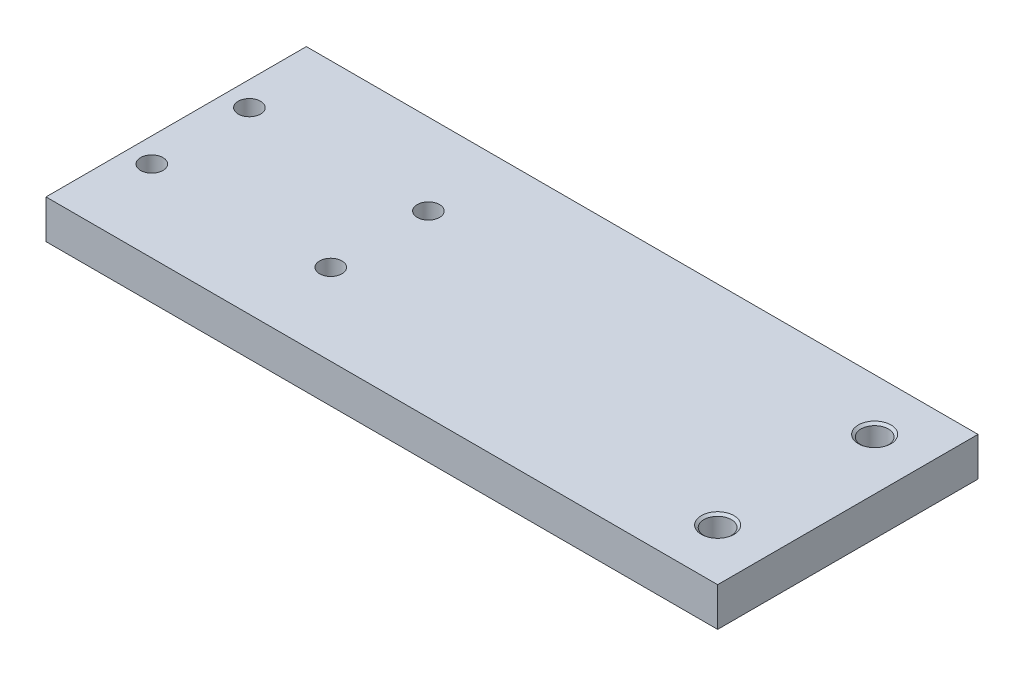
SolidWorks part; units mm, degrees
material "6061 Alloy"
ref_plane "Front" through (0, 0, 0) normal (0, 0, 1) x (1, 0, 0)
ref_plane "Top" through (0, 0, 0) normal (0, 1, 0) x (1, 0, 0)
ref_plane "Right" through (0, 0, 0) normal (1, 0, 0) x (0, 0, -1)
sketch "Sketch1" plane through (0, 0, 0) normal (0, 1, 0) x (1, 0, 0)
  line L1 (0, 0) -> (165.1, 0)
  line L2 (0, 0) -> (0, 64)
  line L3 (0, 64) -> (165.1, 64)
  line L4 (165.1, 0) -> (165.1, 64)
  dimension "D1" = 165.1
  dimension "D2" = 64
extrude "Boss-Extrude1" add sketch "Sketch1" along normal blind 9.525
hole_wizard "1/4 Clearance Hole1" positions "Sketch4" profile "Sketch5" hole size "1/4" standard "ANSI Inch" end condition through all
sketch "Sketch4" plane through (0, 9.525, 0) normal (0, 1, 0) x (1, 0, 0)
  line L0 (152.4, 64) -> (152.4, 51.3) construction
  line L1 (165.1, 64) -> (0, 64) construction
  line L2 (152.4, 51.3) -> (165.1, 51.3) construction
  line L3 (165.1, 0) -> (165.1, 64) construction
  line L5 (165.1, 12.7) -> (152.4, 12.7) construction
  line L6 (152.4, 12.7) -> (152.4, 0) construction
  line L7 (0, 0) -> (165.1, 0) construction
  point P0 (152.4, 51.3)
  point P2 (152.4, 12.7)
  dimension "D1" = 12.7
sketch "Sketch5" plane through (152.4, 9.525, -51.3) normal (1, 0, 0) x (0, 0, 1)
  line L0 (0, 0) -> (0, 9.525)
  line L1 (0, 9.525) -> (3.3782, 9.525)
  line L2 (3.3782, 9.525) -> (3.3782, 0.5328)
  line L3 (3.3782, 0.5328) -> (4.0132, 0)
  line L5 (4.0132, 0) -> (0, 0)
  line L6 (-3.3782, 0.5328) -> (-4.0132, 0) construction
  line L11 (0, -6.35) -> (0, 107.95) construction
  dimension "Thru Hole Dia." = 6.7564
  dimension "Thru Hole Depth" = 9.525
  dimension "Near C'Sink Dia." = 8.0264
  dimension "Near C'Sink Angle" = 100
hole_wizard "CBORE for M5 SHCS1" positions "Sketch8" profile "Sketch7" counterbore size "M5" standard "ANSI Metric" end condition through all
sketch "Sketch8" plane through (0, 0, 0) normal (0, -1, 0) x (-1, 0, 0)
  line L0 (0, 50) -> (0, -50) construction
  line L1 (-6, 44) -> (-6, 20) construction
  line L2 (-6, 20) -> (-6, 32) construction
  line L3 (-6, 32) -> (0, 32) construction
  line L4 (0, 64) -> (0, 0) construction
  point P0 (-6, 44)
  point P2 (-50, 44)
  point P4 (-50, 20)
  point P6 (-6, 20)
  point P25 (0, 0)
  dimension "D1" = 6
  dimension "D2" = 44
  dimension "D3" = 24
sketch "Sketch7" plane through (6, 0, -44) normal (1, 0, 0) x (0, 0, -1)
  line L0 (0, 0) -> (0, 9.525)
  line L1 (0, 9.525) -> (2.75, 9.525)
  line L3 (2.75, 9.525) -> (2.75, 5)
  line L4 (5, 5) -> (2.75, 5)
  line L5 (5, 5) -> (5, 0.021)
  line L6 (5, 0.021) -> (5.025, 0)
  line L7 (5.025, 0) -> (0, 0)
  line L8 (-5, 0.021) -> (-5.025, 0) construction
  line L11 (0, -6.35) -> (0, 107.95) construction
  dimension "Thru Hole Dia." = 5.5
  dimension "Thru Hole Depth" = 9.525
  dimension "C'Bore Dia." = 10
  dimension "C'Bore Depth" = 5
  dimension "Near C'Sink Dia." = 10.05
  dimension "Near C'Sink Angle" = 100
